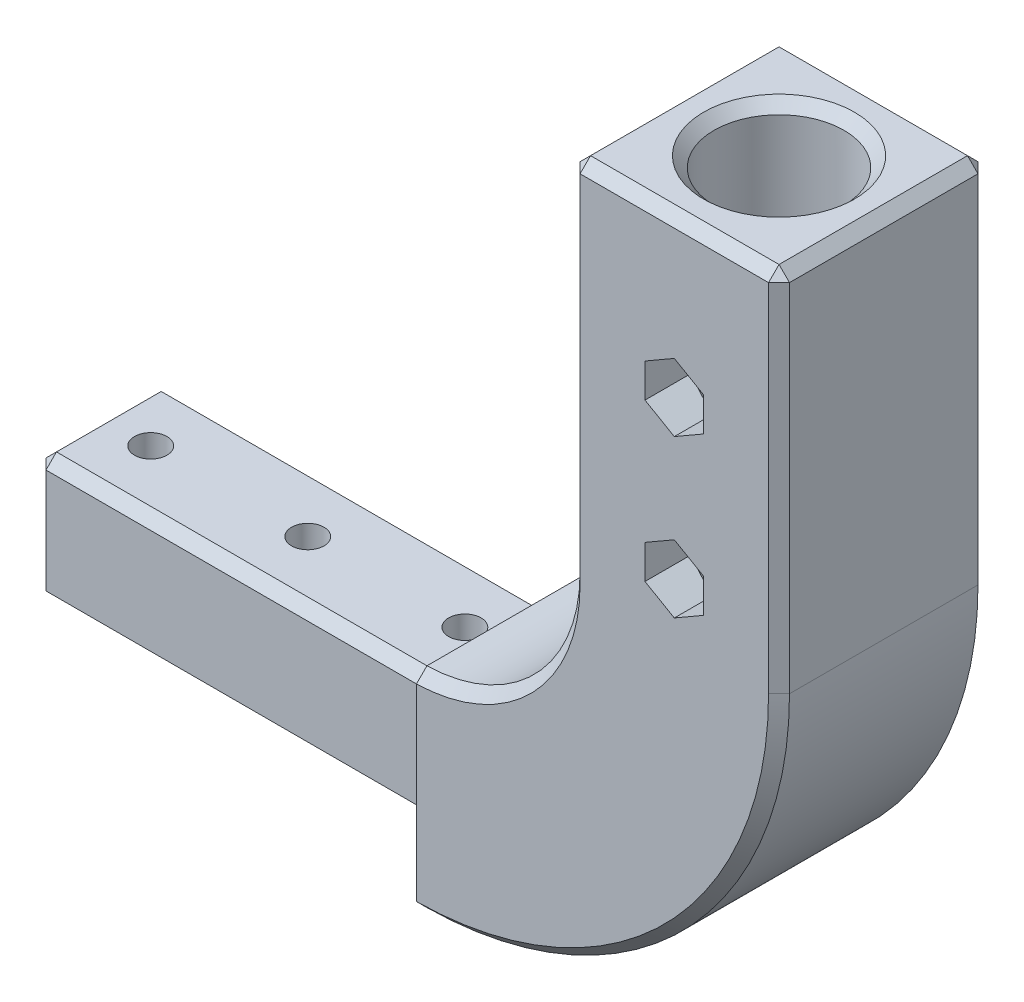
SolidWorks part; units mm, degrees
material "ABS"
ref_plane "前视基准面" through (0, 0, 0) normal (0, 0, 1) x (1, 0, 0)
ref_plane "上视基准面" through (0, 0, 0) normal (0, 1, 0) x (1, 0, 0)
ref_plane "右视基准面" through (0, 0, 0) normal (1, 0, 0) x (0, 0, -1)
other "Configuration Table"
sketch "草图13" plane through (0, 0, 0) normal (0, 0, 1) x (1, 0, 0)
  line L10 (0, 10) -> (45, 10) construction
  line L11 (0, 0) -> (45, 0)
  line L12 (0, 0) -> (0, 20)
  line L13 (0, 20) -> (45, 20)
  line L14 (45, 0) -> (45, 20) construction
  line L15 (45, 10) -> (65, 10) construction
  line L16 (65, 10) -> (65, 30) construction
  line L17 (65, 30) -> (65, 70) construction
  line L18 (55, 70) -> (75, 70)
  line L19 (55, 70) -> (55, 20)
  line L20 (55, 20) -> (45, 20)
  line L21 (75, 70) -> (75, 0)
  line L22 (75, 0) -> (45, 0)
  circle A0 centre (5, 10) radius 1.55 construction
  circle A1 centre (20, 10) radius 1.55 construction
  circle A2 centre (35, 10) radius 1.55 construction
  circle A3 centre (65, 40) radius 1.55
  circle A4 centre (65, 55) radius 1.55
  dimension "D3" = 3.1
  dimension "D4" = 3.1
  dimension "D5" = 3.1
  dimension "D14" = 3.1
  dimension "D16" = 3.1
  dimension "D1" = 45
  dimension "D2" = 20
  dimension "D6" = 5
  dimension "D7" = 15
  dimension "D8" = 15
  dimension "D9" = 20
  dimension "D10" = 20
  dimension "D11" = 40
  dimension "D12" = 10
  dimension "D13" = 10
  dimension "D15" = 10
  dimension "D17" = 15
extrude "凸台-拉伸6" add sketch "草图13" along normal blind 20
sketch "草图14" plane through (0, 0, 0) normal (-1, 0, 0) x (0, 0, 1)
  line L8 (3.9, 16.1) -> (3.9, 3.9)
  line L9 (3.9, 3.9) -> (16.1, 3.9)
  line L10 (16.1, 3.9) -> (16.1, 16.1)
  line L11 (16.1, 16.1) -> (3.9, 16.1)
  line L12 (3.9, 16.1) -> (3.9, 3.9)
  line L13 (3.9, 3.9) -> (16.1, 3.9)
  line L14 (16.1, 3.9) -> (16.1, 16.1)
  line L15 (16.1, 16.1) -> (3.9, 16.1)
  dimension "D1" = 3.9
extrude "切除-拉伸3" [suppressed] cut sketch "草图14" against normal blind 40.1
sketch "草图15" plane through (0, 70, 0) normal (0, 1, 0) x (1, 0, 0)
  line L0 (55, -20) -> (55, 0) construction
  line L1 (75, -20) -> (55, -20) construction
  circle A0 centre (65, -10) radius 6.2
  dimension "D1" = 12.4
  dimension "D2" = 10
  dimension "D3" = 10
extrude "切除-拉伸4" cut sketch "草图15" against normal blind 40.1
sketch "草图16" plane through (0, 20, 0) normal (0, 1, 0) x (1, 0, 0)
  line L0 (0, -10) -> (55, -10) construction
  line L1 (0, -20) -> (0, 0) construction
  line L2 (55, -20) -> (55, 0) construction
  circle A0 centre (5, -10) radius 1.55
  circle A1 centre (20, -10) radius 1.55
  circle A2 centre (35, -10) radius 1.55
  dimension "D3" = 3.1
  dimension "D4" = 3.1
  dimension "D5" = 3.1
  dimension "D1" = 15
  dimension "D2" = 15
  dimension "D6" = 5
extrude "切除-拉伸5" cut sketch "草图16" against normal through all
chamfer "倒角2" [suppressed] distance 10 angle 45
chamfer "倒角4" [suppressed] distance 20 angle 45
chamfer "倒角5" [suppressed] distance 1 angle 45
sketch "草图22" plane through (0, 0, 0) normal (0, 0, -1) x (-1, 0, 0)
  line L4 (-75, 0) -> (-75, 70) construction
  line L6 (0, 0) -> (-75, 0) construction
  line L7 (-55, 70) -> (-55, 20) construction
  line L8 (-75, 35) -> (-75, 70) construction
  line L9 (-75, 70) -> (-55, 70) construction
  line L10 (-55, 70) -> (-55, 45) construction
  line L11 (-30.6101, 20) -> (0, 20) construction
  line L12 (0, 20) -> (0, 0) construction
  line L13 (0, 0) -> (-40, 0) construction
  line L18 (-55, 20) -> (0, 20) construction
sketch "草图24" plane through (0, 0, 0) normal (0, 0, -1) x (-1, 0, 0)
  line L0 (-75, 0) -> (-75, 70) construction
  line L1 (0, 0) -> (-75, 0) construction
  line L2 (0, 0) -> (-40, 0) construction
  line L3 (-75, 35) -> (-75, 0)
  line L4 (-75, 0) -> (-40, 0)
  arc A0 (-75, 35) -> (-40, 0) centre (-40, 35) ccw
  dimension "D1" = 35
  dimension "D2" = 35
  dimension "D3" = 35
extrude "切除-拉伸7" cut sketch "草图24" against normal through all
sketch "草图25" plane through (0, 0, 0) normal (0, 0, -1) x (-1, 0, 0)
  line L0 (-55, 70) -> (-55, 20) construction
  line L1 (-55, 20) -> (0, 20) construction
  line L2 (-55, 34.9953) -> (-55, 20)
  line L3 (-55, 20) -> (-40.3768, 20)
  arc A0 (-55, 34.9953) -> (-40.3768, 20) centre (-40, 34.9953) ccw
  dimension "D1" = 15
  dimension "D2" = 15
  dimension "D3" = 14.9953
extrude "凸台-拉伸8" add sketch "草图25" against normal up to surface (20 mm away) up to face at (43.8927, 29.6788, 20)
chamfer "倒角6" [suppressed] distance 1 angle 45
sketch "草图26" plane through (0, 0, 0) normal (0, -1, 0) x (1, 0, 0)
  line L1 (4.0447, 6.9112) -> (7.1973, 7.6282)
  line L2 (7.1973, 7.6282) -> (8.1526, 10.717)
  line L3 (8.1526, 10.717) -> (5.9553, 13.0888)
  line L4 (5.9553, 13.0888) -> (2.8027, 12.3718)
  line L5 (2.8027, 12.3718) -> (1.8474, 9.283)
  line L6 (1.8474, 9.283) -> (4.0447, 6.9112)
  line L7 (19.0447, 6.9112) -> (22.1973, 7.6282)
  line L8 (22.1973, 7.6282) -> (23.1526, 10.717)
  line L9 (23.1526, 10.717) -> (20.9553, 13.0888)
  line L10 (20.9553, 13.0888) -> (17.8027, 12.3718)
  line L11 (17.8027, 12.3718) -> (16.8474, 9.283)
  line L12 (16.8474, 9.283) -> (19.0447, 6.9112)
  line L13 (34.0447, 6.9112) -> (37.1973, 7.6282)
  line L14 (37.1973, 7.6282) -> (38.1526, 10.717)
  line L15 (38.1526, 10.717) -> (35.9553, 13.0888)
  line L16 (35.9553, 13.0888) -> (32.8027, 12.3718)
  line L17 (32.8027, 12.3718) -> (31.8474, 9.283)
  line L18 (31.8474, 9.283) -> (34.0447, 6.9112)
  circle A0 centre (5, 10) radius 2.8 construction
  circle A1 centre (20, 10) radius 2.8 construction
  circle A2 centre (35, 10) radius 2.8 construction
  dimension "D1" = 5.6
  dimension "D2" = 5.6
  dimension "D3" = 5.6
extrude "切除-拉伸8" cut sketch "草图26" against normal blind 4
sketch "草图27" plane through (0, 0, 20) normal (0, 0, -1) x (-1, 0, 0)
  line L1 (-65, 36.7668) -> (-62.2, 38.3834)
  line L2 (-62.2, 38.3834) -> (-62.2, 41.6166)
  line L3 (-62.2, 41.6166) -> (-65, 43.2332)
  line L4 (-65, 43.2332) -> (-67.8, 41.6166)
  line L5 (-67.8, 41.6166) -> (-67.8, 38.3834)
  line L6 (-67.8, 38.3834) -> (-65, 36.7668)
  line L7 (-65, 51.7668) -> (-62.2, 53.3834)
  line L8 (-62.2, 53.3834) -> (-62.2, 56.6166)
  line L9 (-62.2, 56.6166) -> (-65, 58.2332)
  line L10 (-65, 58.2332) -> (-67.8, 56.6166)
  line L11 (-67.8, 56.6166) -> (-67.8, 53.3834)
  line L12 (-67.8, 53.3834) -> (-65, 51.7668)
  circle A0 centre (-65, 40) radius 2.8 construction
  circle A1 centre (-65, 55) radius 2.8 construction
  dimension "D1" = 5.6
  dimension "D2" = 5.6
extrude "切除-拉伸9" cut sketch "草图27" along normal blind 5
sketch "草图28" plane through (0, 0, 20) normal (0, 0, 1) x (1, 0, 0)
  line L0 (0, 10) -> (20, 10) construction
  line L1 (0, 20) -> (0, 0) construction
  line L3 (12, 12.5) -> (28, 12.5)
  line L4 (10, 10.5) -> (10, 9.5)
  line L5 (12, 7.5) -> (28, 7.5)
  line L6 (30, 10.5) -> (30, 9.5)
  line L7 (10, 12.5) -> (30, 7.5) construction
  line L8 (10, 7.5) -> (30, 12.5) construction
  arc A0 (10, 9.5) -> (12, 7.5) centre (12, 9.5) ccw
  arc A1 (28, 7.5) -> (30, 9.5) centre (28, 9.5) ccw
  arc A2 (28, 12.5) -> (30, 10.5) centre (28, 10.5) cw
  arc A3 (12, 12.5) -> (10, 10.5) centre (12, 10.5) ccw
  dimension "D4" = 2
  dimension "D1" = 20
  dimension "D2" = 20
  dimension "D3" = 5
extrude "切除-拉伸10" [suppressed] cut sketch "草图28" against normal through all
sketch "草图29" plane through (0, 0, 0) normal (-1, 0, 0) x (0, 0, 1)
  line L5 (0, 20) -> (20, 20)
  line L6 (0, 20) -> (0, 0)
  line L7 (0, 0) -> (20, 0)
  line L8 (4, 16) -> (4, 4)
  line L10 (4, 16) -> (4, 4)
  line L16 (20, 20) -> (20, 0)
  line L20 (4, 4) -> (16, 4)
  line L22 (4, 4) -> (16, 4)
  line L24 (16, 4) -> (16, 16)
  line L25 (16, 4) -> (16, 16)
  line L26 (16, 16) -> (4, 16)
  line L27 (16, 16) -> (4, 16)
  dimension "D1" = 4
extrude "切除-拉伸11" cut sketch "草图29" against normal up to vertex (40.3768 mm away)
chamfer "倒角7" distance 1 angle 45 21 edges at (65, 70, 16.2) (0, 10, 16) (20.1884, 4, 16) (0, 16, 10) (0, 4, 10) (20.1884, 4, 4) (0, 10, 4) (20.1884, 16, 4) (20.1884, 16, 16) (64.8816, 10.3849, 20) (64.8816, 10.3849, 0) (50.739, 24.5227, 20) (50.739, 24.5227, 0) (75, 70, 10) (75, 52.5, 20) (65, 70, 20) (75, 52.5, 0) (65, 70, 0) (55, 52.4976, 0) (55, 70, 10) (55, 52.4976, 20)
sketch "草图30" plane through (0, 70, 0) normal (0, 1, 0) x (1, 0, 0)
  line L0 (55, -19) -> (55, -1) construction
  line L1 (55, -9) -> (75, -9)
  line L2 (55, -9) -> (55, -11)
  line L3 (55, -11) -> (75, -11)
  line L4 (75, -9) -> (75, -11)
  line L5 (75, -1) -> (75, -19) construction
  line L6 (75, 0) -> (55, 0) construction
  line L7 (74, -20) -> (56, -20) construction
  dimension "D1" = 9
  dimension "D2" = 9
extrude "切除-拉伸12" [suppressed] cut sketch "草图30" against normal up to surface (40.1 mm away)
